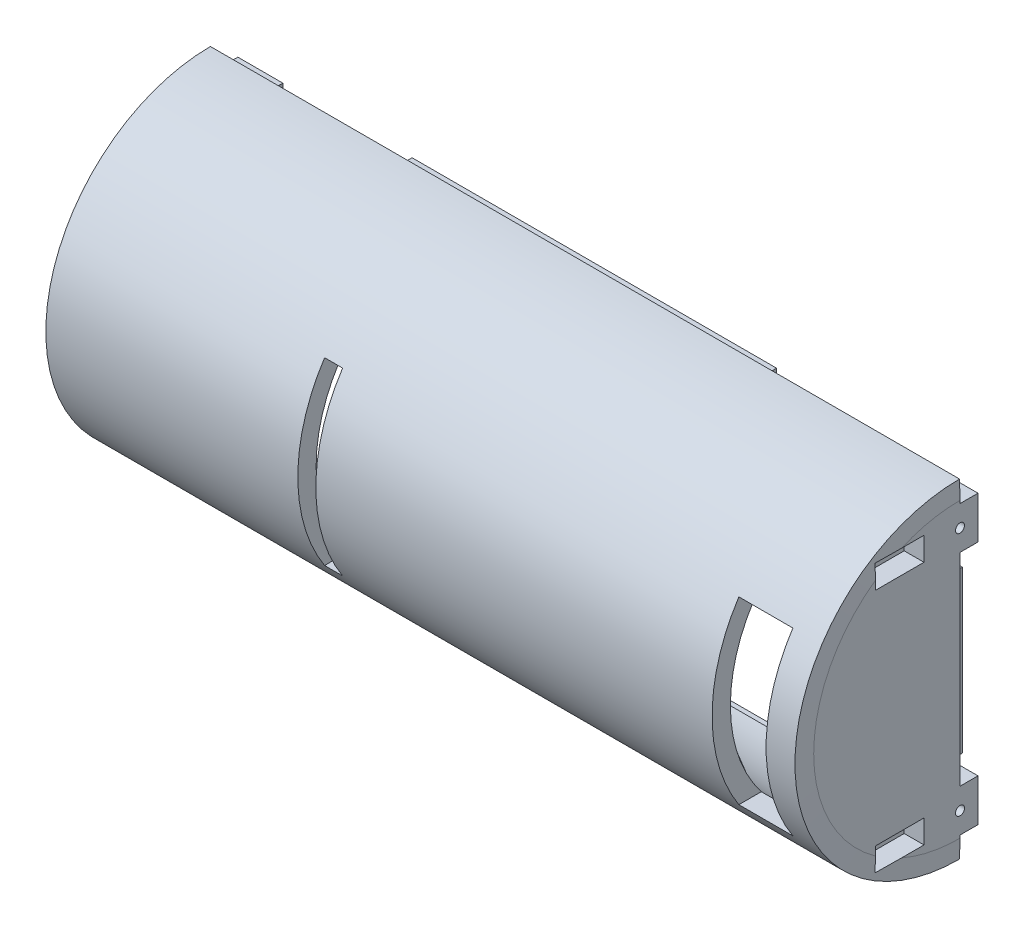
SolidWorks part; units mm, degrees
ref_plane "Front Plane" through (0, 0, 0) normal (0, 0, 1) x (1, 0, 0)
ref_plane "Top Plane" through (0, 0, 0) normal (0, 1, 0) x (1, 0, 0)
ref_plane "Right Plane" through (0, 0, 0) normal (1, 0, 0) x (0, 0, -1)
sketch "Sketch2" plane through (0, 0, 0) normal (0, 0, 1) x (1, 0, 0)
  line L0 (0, 0) -> (0, 40.64)
  line L1 (0, 0) -> (5.08, 0)
  line L2 (5.08, 0) -> (5.08, 40.64)
  line L3 (0, 40.64) -> (0, 45.72)
  line L4 (0, 45.72) -> (25.4, 45.72)
  line L6 (5.08, 40.64) -> (25.4, 40.64)
  line L8 (208.1, 45.72) -> (195.4, 45.72)
  line L9 (195.4, 45.72) -> (25.4, 45.72)
  line L10 (208.2277, 40.64) -> (195.5277, 40.64)
  line L11 (195.5277, 40.64) -> (25.4, 40.64)
  line L12 (208.1, 45.72) -> (208.2277, 40.64)
  dimension "D8" = 5.08
  dimension "D1" = 40.64
  dimension "D2" = 5.08
  dimension "D3" = 40.64
  dimension "D4" = 5.08
  dimension "D5" = 25.4
  dimension "D6" = 170
  dimension "D7" = 12.7
  dimension "D9" = 180
  dimension "D10" = 12.7
revolve "Revolve2" add sketch "Sketch2" angle 180 about L1
sketch "Sketch5" plane through (0, 0, 0) normal (0, 0, -1) x (-1, 0, 0)
  line L0 (-5.08, 40.64) -> (0, 40.64) construction
  line L1 (-3.79, 40.64) -> (-1.29, 40.64)
  line L2 (-3.79, 40.64) -> (-3.79, 28.14)
  line L3 (-3.79, 28.14) -> (-1.29, 28.14)
  line L4 (-1.29, 40.64) -> (-1.29, 28.14)
  line L5 (0, -45.72) -> (0, 45.72) construction
  line L6 (-5.08, 40.64) -> (-5.08, 45.72) construction
  line L7 (-208.1, 45.72) -> (0, 45.72) construction
  line L8 (-154.7389, -41.93) -> (-154.7389, -44.43)
  line L9 (-5.08, 44.43) -> (-17.58, 44.43)
  line L10 (-5.08, 44.43) -> (-5.08, 41.93)
  line L11 (-5.08, 41.93) -> (-17.58, 41.93)
  line L12 (-17.58, 44.43) -> (-17.58, 41.93)
  line L13 (-154.7389, -44.43) -> (-53.4889, -44.43)
  line L14 (-53.4889, -44.43) -> (-53.4889, -41.93)
  line L15 (-53.4889, -41.93) -> (-154.7389, -41.93)
  line L16 (-312.3416, -45.72) -> (104.1139, -45.72) construction
  line L17 (-53.4889, -41.93) -> (-53.4889, -45.72) construction
  line L18 (-53.4889, -44.43) -> (-53.4889, -40.64) construction
  line L19 (104.1139, -40.64) -> (-312.3416, -40.64) construction
  line L20 (-154.7389, -40.64) -> (-154.7389, -44.43) construction
  line L21 (-154.7389, -41.93) -> (-154.7389, -45.72) construction
  line L22 (0, 0) -> (-208.2277, 0) construction
  line L23 (-208.2277, -40.64) -> (-208.2277, 40.64) construction
  line L24 (-53.4889, 44.43) -> (-53.4889, 41.93)
  line L25 (-154.7389, 44.43) -> (-53.4889, 44.43)
  line L26 (-154.7389, 41.93) -> (-154.7389, 44.43)
  line L27 (-53.4889, 41.93) -> (-154.7389, 41.93)
  line L28 (-5.08, -41.93) -> (-17.58, -41.93)
  line L29 (-17.58, -44.43) -> (-17.58, -41.93)
  line L30 (-5.08, -44.43) -> (-17.58, -44.43)
  line L31 (-5.08, -44.43) -> (-5.08, -41.93)
  line L32 (-3.79, -28.14) -> (-1.29, -28.14)
  line L33 (-1.29, -40.64) -> (-1.29, -28.14)
  line L34 (-3.79, -40.64) -> (-1.29, -40.64)
  line L35 (-3.79, -40.64) -> (-3.79, -28.14)
  point P9 (-2.54, 40.64)
  point P10 (-2.54, 40.64)
  point P18 (-5.08, 43.18)
  point P19 (-5.08, 43.18)
  point P26 (-104.1139, -45.72)
  point P27 (-104.1139, -41.93)
  dimension "D1" = 12.5
  dimension "D2" = 2.5
  dimension "D3" = 12.5
  dimension "D4" = 2.5
  dimension "D5" = 2.5
  dimension "D6" = 2.5
  dimension "D7" = 101.25
extrude "Boss-Extrude1" add sketch "Sketch5" along normal blind 2.54 contours L15 L8 L13 L14 | L10 L9 L12 L11 | L2 L1 L4 L3 | L32 L33 L34 L35 | L28 L29 L30 L31 | L24 L27 L26 L25
sketch "Sketch7" plane through (0, 0, 0) normal (-1, 0, 0) x (0, 0, 1)
  line L0 (0, 25) -> (0, -25)
  line L1 (0, 25) -> (20, 25)
  line L2 (0, -25) -> (20, -25)
  line L3 (20, 25) -> (20, -25)
  line L4 (0, -45.72) -> (0, 45.72) construction
  point P6 (0, 0)
  dimension "D1" = 50
  dimension "D2" = 20
extrude "Cut-Extrude1" cut sketch "Sketch7" against normal blind 7
sketch "Sketch8" plane through (0, 0, 0) normal (0, 0, -1) x (-1, 0, 0)
  line L0 (-208.1, 45.72) -> (0, 45.72) construction
  line L1 (-13.08, 45.72) -> (-18.08, 45.72)
  line L2 (-13.08, 45.72) -> (-13.08, -45.72)
  line L3 (-13.08, -45.72) -> (-18.08, -45.72)
  line L4 (-18.08, 45.72) -> (-18.08, -45.72)
  line L5 (-5.08, 40.64) -> (-5.08, 25) construction
  line L8 (-208.1, -45.72) -> (0, -45.72) construction
  dimension "D1" = 5
  dimension "D3" = 8
extrude "Boss-Extrude3" add sketch "Sketch8" against normal up to next
sketch "Sketch9" plane through (5.08, 0, 0) normal (1, 0, 0) x (0, 0, -1)
  line L1 (-0.8418, 37.9918) -> (-6.9711, 37.9918)
  line L2 (-0.8418, 37.9918) -> (-0.8418, 29.9132)
  line L3 (-0.8418, 29.9132) -> (-6.9711, 29.9132)
  line L4 (-6.9711, 37.9918) -> (-6.9711, 29.9132)
extrude "Boss-Extrude4" add sketch "Sketch9" along normal blind 2
sketch "Sketch12" plane through (13.08, 0, 0) normal (-1, 0, 0) x (0, 0, 1)
  line L0 (23.64, 33.0569) -> (23.64, -33.0569)
  line L1 (20, -25) -> (20, 25) construction
  arc A0 (23.64, 33.0569) -> (23.64, -33.0569) centre (0, 0) cw
  arc A2 (0, -40.64) -> (0, 40.64) centre (0, 0) ccw construction
  point P3 (23.64, 0)
  point P5 (40.64, 0)
  dimension "D1" = 17
extrude "Boss-Extrude7" add sketch "Sketch12" along normal up to surface (8 mm away) up to face at (5.08, 0, 13.44)
sketch "Sketch13" plane through (0, 0, 0) normal (0, 0, -1) x (-1, 0, 0)
  line L1 (-82.54, 27.5) -> (-152.54, 27.5)
  line L2 (-82.54, 27.5) -> (-82.54, -27.5)
  line L3 (-82.54, -27.5) -> (-152.54, -27.5)
  line L4 (-152.54, 27.5) -> (-152.54, -27.5)
  line L5 (-80, 30.04) -> (-155.08, 30.04)
  line L6 (-80, 30.04) -> (-80, -30.04)
  line L7 (-80, -30.04) -> (-155.08, -30.04)
  line L8 (-155.08, 30.04) -> (-155.08, -30.04)
  line L9 (-80, 40.64) -> (-80, -40.64) construction
  line L11 (-18.08, 40.64) -> (-208.2277, 40.64) construction
  line L12 (-18.08, -40.64) -> (-208.2277, -40.64) construction
  line L13 (0, 25) -> (0, 45.72) construction
  dimension "D1" = 55
  dimension "D2" = 70
  dimension "D3" = 2.54
  dimension "D4" = 2.54
  dimension "D5" = 2.54
  dimension "D6" = 2.54
  dimension "D7" = 80
extrude "Boss-Extrude8" add sketch "Sketch13" against normal up to surface (29.9226 mm away)
sketch "Sketch14" plane through (0, 0, 0) normal (0, 0, -1) x (-1, 0, 0)
  line L1 (-80, 30.04) -> (-155.08, 30.04)
  line L2 (-80, 30.04) -> (-80, -30.04)
  line L3 (-80, -30.04) -> (-155.08, -30.04)
  line L4 (-155.08, 30.04) -> (-155.08, -30.04)
extrude "Cut-Extrude3" cut sketch "Sketch14" against normal blind 11
sketch "Sketch15" plane through (0, 0, 11) normal (0, 0, -1) x (-1, 0, 0)
  line L1 (-82.54, 27.5) -> (-152.54, 27.5)
  line L2 (-82.54, 27.5) -> (-82.54, -27.5)
  line L3 (-82.54, -27.5) -> (-152.54, -27.5)
  line L4 (-152.54, 27.5) -> (-152.54, -27.5)
extrude "Boss-Extrude9" add sketch "Sketch15" against normal up to next
sketch "Sketch17" plane through (0, 0, 11) normal (0, 0, -1) x (-1, 0, 0)
  line L0 (-80, 30.04) -> (-155.08, 30.04) construction
  line L1 (-82.54, 27.5) -> (-152.54, 27.5)
  line L2 (-82.54, 27.5) -> (-82.54, -27.5)
  line L3 (-82.54, -27.5) -> (-152.54, -27.5)
  line L4 (-152.54, 27.5) -> (-152.54, 19.5)
  line L5 (-155.08, 30.04) -> (-155.08, -30.04) construction
  line L6 (-155.08, -30.04) -> (-80, -30.04) construction
  line L7 (-80, -30.04) -> (-80, 30.04) construction
  line L8 (-152.54, 5.5) -> (-152.54, -13.5)
  line L9 (-152.54, 19.5) -> (-155.08, 19.5)
  line L11 (-152.54, 5.5) -> (-155.08, 5.5)
  line L12 (-155.08, 19.5) -> (-155.08, 5.5)
  line L13 (-152.54, -24.5) -> (-155.08, -24.5)
  line L15 (-152.54, -13.5) -> (-155.08, -13.5)
  line L16 (-155.08, -24.5) -> (-155.08, -13.5)
  line L17 (-152.54, -24.5) -> (-152.54, -27.5)
  dimension "D1" = 2.54
  dimension "D2" = 2.54
  dimension "D3" = 2.54
  dimension "D4" = 2.54
  dimension "D5" = 8
  dimension "D6" = 22
  dimension "D7" = 14
  dimension "D8" = 3
extrude "Cut-Extrude5" cut sketch "Sketch17" against normal blind 15
sketch "Sketch18" plane through (18.08, 0, 0) normal (1, 0, 0) x (0, 0, -1)
  line L0 (0, 40.64) -> (0, -40.64) construction
  line L1 (0, 17.9952) -> (-12, 17.9952)
  line L2 (0, 17.9952) -> (0, -38.0048)
  line L3 (0, -38.0048) -> (-12, -38.0048)
  line L4 (-12, 17.9952) -> (-12, -38.0048)
  dimension "D1" = 12
  dimension "D2" = 56
  dimension "D3" = 2.6352
extrude "Cut-Extrude6" cut sketch "Sketch18" against normal up to next
sketch "Sketch23" plane through (0, 0, 0) normal (0, 0, -1) x (-1, 0, 0)
  line L0 (-18.08, -40.64) -> (-208.2277, -40.64) construction
  line L1 (-208.2277, 40.64) -> (-202.2277, 40.64)
  line L2 (-208.2277, 40.64) -> (-208.2277, -40.64)
  line L3 (-208.2277, -40.64) -> (-202.2277, -40.64)
  line L4 (-202.2277, 40.64) -> (-202.2277, -40.64)
  dimension "D1" = 6
extrude "Boss-Extrude10" add sketch "Sketch23" against normal up to surface
sketch "Sketch26" plane through (0, 0, 0) normal (0, 0, -1) x (-1, 0, 0)
  line L0 (-202.2277, -40.64) -> (-202.2277, 40.64) construction
  line L1 (-202.2277, 39.875) -> (-208.2277, 39.875)
  line L2 (-202.2277, 39.875) -> (-202.2277, 28.125)
  line L3 (-202.2277, 28.125) -> (-208.2277, 28.125)
  line L4 (-208.2277, 39.875) -> (-208.2277, 28.125)
  line L5 (-208.2277, 40.64) -> (-208.2277, -40.64) construction
  line L7 (-202.2277, -39.875) -> (-208.2277, -39.875)
  line L8 (-202.2277, -39.875) -> (-202.2277, -28.125)
  line L9 (-202.2277, -28.125) -> (-208.2277, -28.125)
  line L10 (-208.2277, -39.875) -> (-208.2277, -28.125)
  point P8 (-208.2277, 0)
  point P9 (-208.2277, 34)
  point P14 (-208.2277, -34)
  dimension "D1" = 34
  dimension "D2" = 11.75
  dimension "D3" = 34
  dimension "D4" = 11.75
extrude "Boss-Extrude11" add sketch "Sketch26" along normal blind 5
sketch "Sketch27" plane through (208.2277, 0, 0) normal (1, 0, 0) x (0, 0, -1)
  line L0 (5, -28.125) -> (5, -39.875) construction
  line L1 (-23.5, -30.75) -> (-10, -30.75)
  line L2 (-23.5, -30.75) -> (-23.5, -37.25)
  line L3 (-23.5, -37.25) -> (-10, -37.25)
  line L4 (-10, -30.75) -> (-10, -37.25)
  line L5 (-23.5, 37.25) -> (-10, 37.25)
  line L6 (-23.5, 37.25) -> (-23.5, 30.75)
  line L7 (-23.5, 30.75) -> (-10, 30.75)
  line L8 (-10, 37.25) -> (-10, 30.75)
  line L9 (5, 39.875) -> (5, 28.125) construction
  line L10 (0, 28.125) -> (0, -28.125) construction
  point P8 (-16.75, -30.75)
  point P9 (-16.75, 30.75)
  point P10 (-10, -34)
  point P13 (5, -34)
  point P14 (-10, 34)
  point P17 (5, 34)
  dimension "D1" = 13.5
  dimension "D2" = 6.5
  dimension "D3" = 10
extrude "Cut-Extrude7" cut sketch "Sketch27" against normal blind 5.5
sketch "Sketch28" plane through (208.2277, 0, 0) normal (1, 0, 0) x (0, 0, -1)
  line L0 (5, 39.875) -> (5, 28.125) construction
  line L1 (5, -28.125) -> (5, -39.875) construction
  line L2 (0, 28.125) -> (0, -28.125) construction
  circle A0 centre (0, 34) radius 1.25
  circle A1 centre (0, -34) radius 1.25
  point P4 (0, 0)
  point P7 (5, 34)
  point P8 (0, 0)
  point P11 (5, -34)
  point P12 (0, 0)
  point P15 (0, 0)
  dimension "D1" = 2.5
extrude "Cut-Extrude8" cut sketch "Sketch28" against normal up to next
sketch "Sketch29" plane through (202.2277, 0, 0) normal (-1, 0, 0) x (0, 0, 1)
  line L0 (0, -28.125) -> (0, 28.125) construction
  circle A0 centre (0, -34) radius 3.125
  circle A1 centre (0, 34) radius 3.125
  point P6 (0, 0)
  point P9 (0, 0)
  dimension "D1" = 6.25
extrude "Cut-Extrude9" cut sketch "Sketch29" against normal blind 2.5
sketch "Sketch30" plane through (0, 0, 11) normal (0, 0, -1) x (-1, 0, 0)
  line L0 (-80, -30.04) -> (-80, 30.04) construction
  line L1 (-70, 25) -> (-75, 25)
  line L2 (-70, 25) -> (-70, -25)
  line L3 (-70, -25) -> (-75, -25)
  line L4 (-75, 25) -> (-75, -25)
  line L5 (-155.08, 5.5) -> (-155.08, -13.5) construction
  line L6 (-185.08, 25) -> (-200.08, 25)
  line L7 (-185.08, 25) -> (-185.08, -25)
  line L8 (-185.08, -25) -> (-200.08, -25)
  line L9 (-200.08, 25) -> (-200.08, -25)
  point P4 (-75, 0)
  point P7 (-80, 0)
  point P12 (-185.08, 0)
  dimension "D1" = 50
  dimension "D2" = 5
  dimension "D3" = 5
  dimension "D4" = 50
  dimension "D5" = 15
  dimension "D6" = 30
extrude "Cut-Extrude10" cut sketch "Sketch30" against normal through all
sketch "Sketch32" plane through (0, 0, 0) normal (0, 0, -1) x (-1, 0, 0)
  line L0 (-208.2277, 28.125) -> (-202.2277, 28.125) construction
  line L5 (-206.3527, 22.375) -> (-204.1027, 22.375)
  line L6 (-206.3527, 22.375) -> (-206.3527, -22.375)
  line L7 (-206.3527, -22.375) -> (-204.1027, -22.375)
  line L8 (-204.1027, 22.375) -> (-204.1027, -22.375)
  line L9 (-202.2277, -28.125) -> (-202.2277, 28.125) construction
  point P4 (-205.2277, 22.375)
  point P7 (-205.2277, 28.125)
  point P8 (-204.1027, 0)
  point P11 (-202.2277, 0)
  dimension "D1" = 44.75
  dimension "D2" = 2.25
extrude "Boss-Extrude12" add sketch "Sketch32" along normal blind 2.54
ref_plane "Plane1" through (0, 0, -10) normal (0, 0, -1) x (-1, 0, 0)
